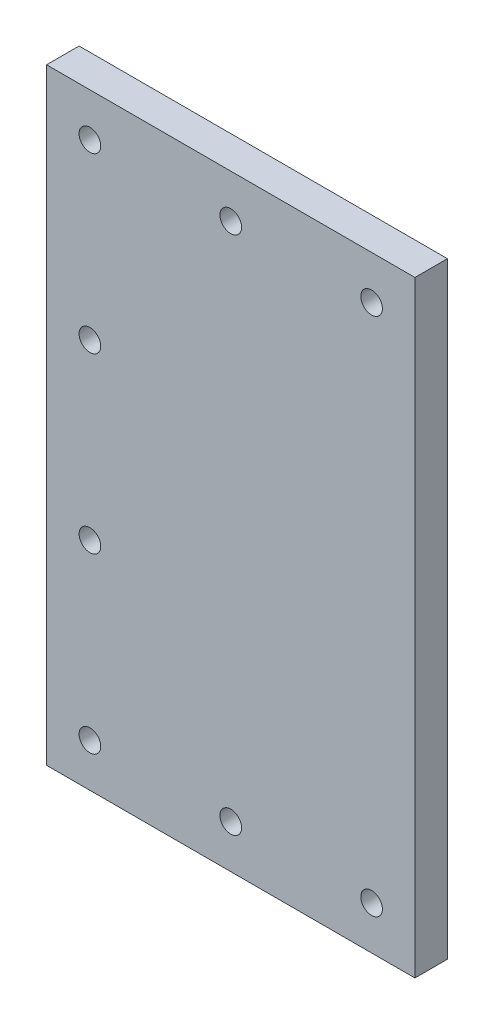
SolidWorks part; units mm, degrees
ref_plane "Front" through (0, 0, 0) normal (0, 0, 1) x (1, 0, 0)
ref_plane "Top" through (0, 0, 0) normal (0, 1, 0) x (1, 0, 0)
ref_plane "Right" through (0, 0, 0) normal (1, 0, 0) x (0, 0, -1)
sketch "Sketch1" plane through (0, 0, 0) normal (0, 0, 1) x (1, 0, 0)
  line L1 (42.5, -70) -> (-42.5, -70)
  line L2 (42.5, -70) -> (42.5, 70)
  line L3 (42.5, 70) -> (-42.5, 70)
  line L4 (-42.5, -70) -> (-42.5, 70)
  line L5 (42.5, -70) -> (-42.5, 70) construction
  line L6 (42.5, 70) -> (-42.5, -70) construction
  point P0 (0, 0)
  dimension "D1" = 85
  dimension "D2" = 140
extrude "Boss-Extrude1" add sketch "Sketch1" along normal mid plane 7.5
sketch "Sketch2" plane through (0, 0, 3.75) normal (0, 0, 1) x (1, 0, 0)
  line L0 (-32.5, 60) -> (-32.5, 70) construction
  line L1 (42.5, 70) -> (-42.5, 70) construction
  line L2 (-32.5, 60) -> (-42.5, 60) construction
  line L3 (-42.5, 70) -> (-42.5, -70) construction
  circle A0 centre (-32.5, 60) radius 2.5
  dimension "D1" = 5
  dimension "D2" = 10
  dimension "D3" = 10
extrude "Cut-Extrude1" cut sketch "Sketch2" against normal through all both and the other way through all
pattern_linear "LPattern1" count 3 spacing 32.5 along (1, 0, 0) count 4 spacing 40 along (0, -1, 0) skipping (1, 1), (1, 2), (2, 1), (2, 2) of "Cut-Extrude1"
